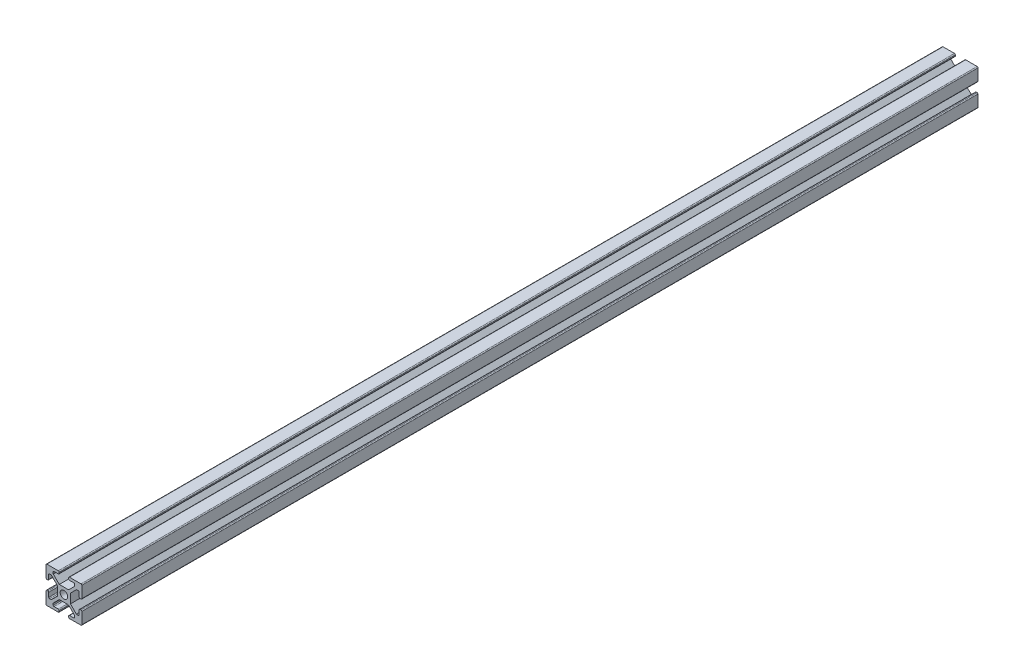
SolidWorks part; units mm, degrees
material "6061-T6 (SS)"
ref_plane "Front Plane" through (0, 0, 0) normal (0, 0, 1) x (1, 0, 0)
ref_plane "Top Plane" through (0, 0, 0) normal (0, 1, 0) x (1, 0, 0)
ref_plane "Right Plane" through (0, 0, 0) normal (1, 0, 0) x (0, 0, -1)
sketch "Sketch2" plane through (0, 0, 0) normal (0, 0, 1) x (1, 0, 0)
  line L0 (0, 3.66) -> (2.5993, 3.66)
  line L1 (0, 0) -> (3.66, 0)
  line L2 (0, 0) -> (0, 3.66)
  line L3 (2.63, 10) -> (10, 10)
  line L4 (10, 2.63) -> (10, 10)
  line L5 (3.66, 2.5993) -> (3.66, 0)
  line L6 (3.66, 3.66) -> (10, 10) construction
  line L7 (2.5993, 3.66) -> (5.995, 7.0557)
  line L8 (5.995, 7.0557) -> (5.995, 8.5)
  line L9 (5.995, 8.5) -> (2.63, 8.5)
  line L10 (2.63, 8.5) -> (2.63, 10)
  line L11 (3.66, 2.5993) -> (7.0557, 5.995)
  line L12 (7.0557, 5.995) -> (8.5, 5.995)
  line L13 (8.5, 5.995) -> (8.5, 2.63)
  line L14 (8.5, 2.63) -> (10, 2.63)
  line L15 (5.995, 7.0557) -> (6.5253, 6.5253) construction
  line L16 (6.5253, 6.5253) -> (7.0557, 5.995) construction
  line L17 (0, 3.66) -> (0, 10) construction
  line L18 (3.66, 0) -> (10, 0) construction
  line L19 (0, 10) -> (2.63, 10) construction
  line L20 (10, 0) -> (10, 2.63) construction
  line L21 (2.5993, 3.66) -> (3.66, 3.66) construction
  line L22 (3.66, 3.66) -> (3.66, 2.5993) construction
  dimension "D1" = 10
  dimension "D2" = 3.66
  dimension "D3" = 1.5
  dimension "D4" = 2.63
  dimension "D5" = 1.5
  dimension "D6" = 5.995
extrude "Boss-Extrude1" add sketch "Sketch2" along normal mid plane 500
fillet "Fillet1" radius 0.5 9 edges at (7.0557, 5.995, 0) (5.995, 7.0557, 0) (5.995, 8.5, 0) (8.5, 5.995, 0) (2.63, 8.5, 0) (2.63, 10, 0) (8.5, 2.63, 0) (10, 2.63, 0) (10, 10, 0)
pattern_circular "CirPattern3" count 4 over 360 about axis through (0, 0, 250) along (0, 0, -1) of "Fillet1", "Boss-Extrude1"
sketch "Sketch3" plane through (0, 0, 250) normal (0, 0, 1) x (1, 0, 0)
  circle A0 centre (0, 0) radius 2.095
  dimension "D1" = 4.19
extrude "Cut-Extrude1" cut sketch "Sketch3" against normal through all
